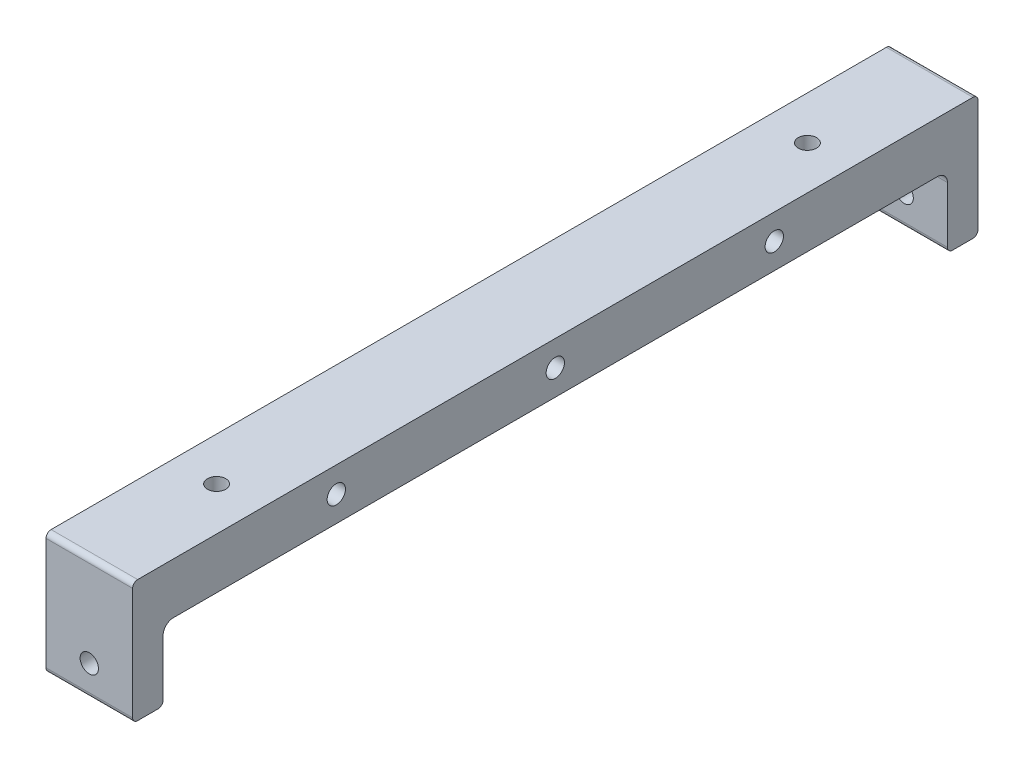
SolidWorks part; units mm, degrees
material "6061 Alloy"
ref_plane "Frontal" through (0, 0, 0) normal (0, 0, 1) x (1, 0, 0)
ref_plane "Superior" through (0, 0, 0) normal (0, 1, 0) x (1, 0, 0)
ref_plane "Direito" through (0, 0, 0) normal (1, 0, 0) x (0, 0, -1)
sketch "Sketch1" plane through (0, 0, 0) normal (0, 0, 1) x (1, 0, 0)
  line L1 (-4.25, -6) -> (4.25, -6)
  line L2 (-4.25, -6) -> (-4.25, 6)
  line L3 (-4.25, 6) -> (4.25, 6)
  line L4 (4.25, -6) -> (4.25, 6)
  line L5 (-4.25, -6) -> (4.25, 6) construction
  line L6 (-4.25, 6) -> (4.25, -6) construction
  point P0 (0, 0)
  dimension "D1" = 8.5
  dimension "D2" = 12
extrude "Boss-Extrude1" add sketch "Sketch1" along normal mid plane 83
sketch "Sketch2" plane through (4.25, 0, 0) normal (1, 0, 0) x (0, 0, -1)
  line L0 (-37.5, 1) -> (37.5, 1)
  line L1 (38.5, 0) -> (38.5, -6)
  line L2 (-41.5, -6) -> (41.5, -6) construction
  line L3 (38.5, -6) -> (-38.5, -6)
  line L4 (-38.5, -6) -> (-38.5, 0)
  line L5 (-41.5, 6) -> (41.5, 6) construction
  line L6 (-41.5, -6) -> (-41.5, 6) construction
  line L7 (41.5, -6) -> (41.5, 6) construction
  arc A0 (37.5, 1) -> (38.5, 0) centre (37.5, 0) cw
  arc A1 (-37.5, 1) -> (-38.5, 0) centre (-37.5, 0) ccw
  dimension "D4" = 1
  dimension "D5" = 1
  dimension "D1" = 5
  dimension "D2" = 3
  dimension "D3" = 3
extrude "Cut-Extrude1" cut sketch "Sketch2" against normal through all
hole_wizard "M1.6 Hole1-FixingPCB" positions "Sketch6" profile "Sketch5" countersink size "M1.6" standard "DIN" end condition through all
sketch "Sketch6" plane through (-4.25, 0, 0) normal (-1, 0, 0) x (0, 0, 1)
  line L0 (41.5, 6) -> (-41.5, 6) construction
  line L1 (-41.5, 6) -> (-41.5, -6) construction
  line L2 (41.5, -6) -> (41.5, 6) construction
  point P0 (-21.5, 3.5)
  point P2 (21.5, 3.5)
  point P10 (41.5, 0)
  dimension "D1" = 2.5
  dimension "D2" = 20
  dimension "D3" = 20
sketch "Sketch5" plane through (-4.25, 3.5, -21.5) normal (0, 1, 0) x (0, 0, 1)
  line L0 (0, 0) -> (0, 8.5)
  line L1 (0, 8.5) -> (0.9, 8.5)
  line L2 (0.9, 8.5) -> (0.9, 0.9)
  line L3 (0.9, 0.9) -> (1.8, 0)
  line L5 (1.8, 0) -> (0, 0)
  line L6 (-0.9, 0.9) -> (-1.8, 0) construction
  line L11 (0, -6.35) -> (0, 107.95) construction
  dimension "Thru Hole Dia." = 1.8
  dimension "Thru Hole Depth" = 8.5
  dimension "Near C'Sink Dia." = 3.6
  dimension "Near C'Sink Angle" = 90
fillet "Fillet1" radius 0.5 6 edges at (0, -6, 38.5) (0, -6, 41.5) (0, -6, -38.5) (0, -6, -41.5) (0, 6, 41.5) (0, 6, -41.5)
hole_wizard "M1.6 Hole2-IntUnion" positions "Sketch8" profile "Sketch7" hole size "M1.6" standard "DIN"
sketch "Sketch8" plane through (0, 0, 41.5) normal (0, 0, 1) x (1, 0, 0)
  line L0 (4.25, -6) -> (-4.25, -6) construction
  point P0 (0, -3)
  dimension "D1" = 3
sketch "Sketch7" plane through (0, -3, 41.5) normal (1, 0, 0) x (0, -1, 0)
  line L0 (0, 0) -> (0, 200.5408)
  line L1 (0, 200.5408) -> (0.9, 200)
  line L2 (0.9, 200) -> (0.9, 0)
  line L5 (0.9, 0) -> (0, 0)
  line L10 (0, 200.5408) -> (-0.9, 200) construction
  line L11 (0, -6.35) -> (0, 107.95) construction
  dimension "Hole Dia." = 1.8
  dimension "Hole Depth" = 200
  dimension "Drill Angle" = 118
hole_wizard "M1.6 Hole3-ExtUnion" positions "Sketch10" profile "Sketch9" hole size "M1.6" standard "DIN"
sketch "Sketch10" plane through (-4.25, 0, 0) normal (-1, 0, 0) x (0, 0, 1)
  line L0 (41, 6) -> (-41, 6) construction
  line L1 (41.5, 5.5) -> (41.5, -5.5) construction
  line L2 (-41.5, 5.5) -> (-41.5, -5.5) construction
  point P0 (-35.5, 3.5)
  point P2 (35.5, 3.5)
  dimension "D1" = 2.5
  dimension "D2" = 6
  dimension "D3" = 6
sketch "Sketch9" plane through (-4.25, 3.5, -35.5) normal (0, 1, 0) x (0, 0, 1)
  line L0 (0, 0) -> (0, 3.5408)
  line L1 (0, 3.5408) -> (0.9, 3)
  line L2 (0.9, 3) -> (0.9, 0)
  line L5 (0.9, 0) -> (0, 0)
  line L10 (0, 3.5408) -> (-0.9, 3) construction
  line L11 (0, -6.35) -> (0, 107.95) construction
  dimension "Hole Dia." = 1.8
  dimension "Hole Depth" = 3
  dimension "Drill Angle" = 118
hole_wizard "M1.6 Hole4-TopUnion" positions "Sketch13" profile "Sketch12" hole size "M1.6" standard "DIN"
sketch "Sketch13" plane through (4.25, 0, 0) normal (1, 0, 0) x (0, 0, -1)
  line L0 (-41, 6) -> (41, 6) construction
  point P0 (0, 3.5)
  dimension "D1" = 2.5
sketch "Sketch12" plane through (4.25, 3.5, 0) normal (0, 1, 0) x (0, 0, -1)
  line L0 (0, 0) -> (0, 3.5408)
  line L1 (0, 3.5408) -> (0.9, 3)
  line L2 (0.9, 3) -> (0.9, 0)
  line L5 (0.9, 0) -> (0, 0)
  line L10 (0, 3.5408) -> (-0.9, 3) construction
  line L11 (0, -6.35) -> (0, 107.95) construction
  dimension "Hole Dia." = 1.8
  dimension "Hole Depth" = 3
  dimension "Drill Angle" = 118
hole_wizard "M1.6 Clearance Hole1" positions "Sketch15" profile "Sketch14" hole size "M1.6" standard "DIN"
sketch "Sketch15" plane through (0, 6, 0) normal (0, 1, 0) x (1, 0, 0)
  line L0 (4.25, -41) -> (4.25, 41) construction
  line L1 (-4.25, 41.5) -> (4.25, 41.5) construction
  line L2 (4.25, -41.5) -> (-4.25, -41.5) construction
  point P0 (0, 29)
  point P2 (0, -29)
  dimension "D1" = 4.25
  dimension "D2" = 12.5
  dimension "D3" = 12.5
sketch "Sketch14" plane through (0, 6, -29) normal (1, 0, 0) x (0, 0, 1)
  line L0 (0, 0) -> (0, 3.5408)
  line L1 (0, 3.5408) -> (0.9, 3)
  line L2 (0.9, 3) -> (0.9, 0)
  line L5 (0.9, 0) -> (0, 0)
  line L10 (0, 3.5408) -> (-0.9, 3) construction
  line L11 (0, -6.35) -> (0, 107.95) construction
  dimension "Hole Dia." = 1.8
  dimension "Hole Depth" = 3
  dimension "Drill Angle" = 118
